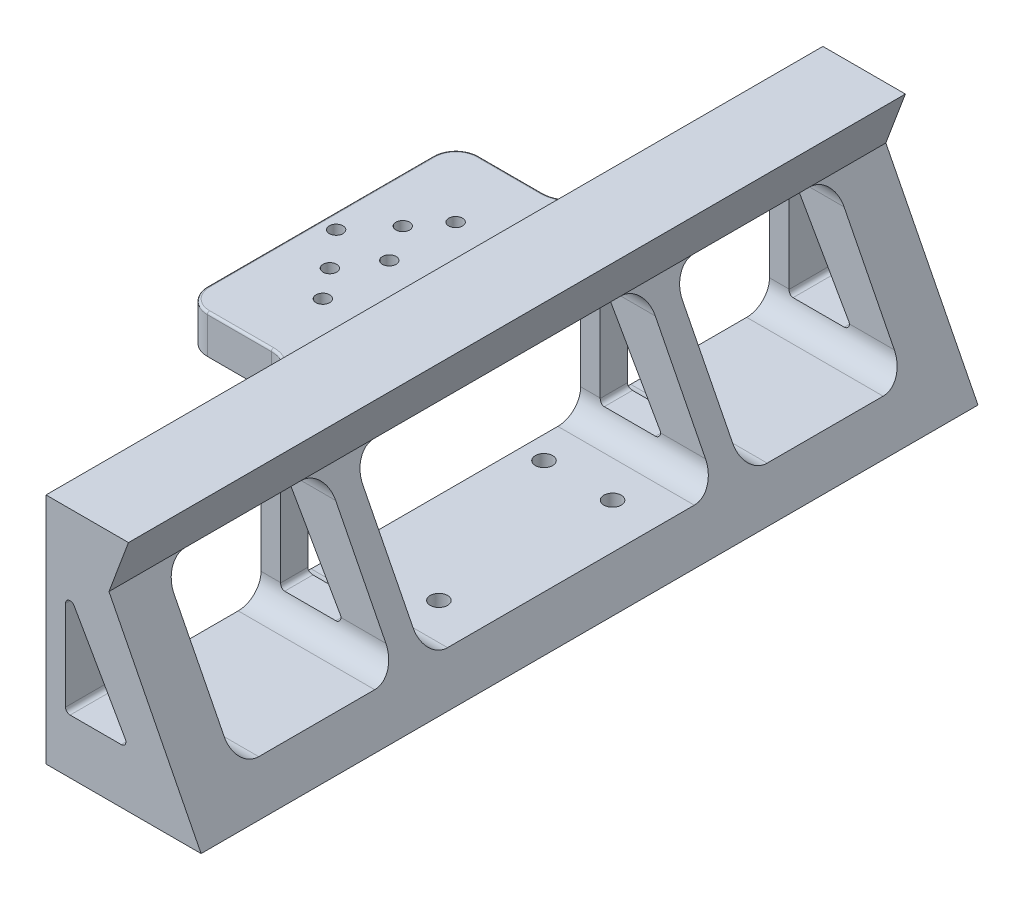
SolidWorks part; units mm, degrees
ref_plane "前视基准面" through (0, 0, 0) normal (0, 0, 1) x (1, 0, 0)
ref_plane "上视基准面" through (0, 0, 0) normal (0, 1, 0) x (1, 0, 0)
ref_plane "右视基准面" through (0, 0, 0) normal (1, 0, 0) x (0, 0, -1)
other "Configuration Table"
sketch "草图1" plane through (0, 0, 0) normal (0, 0, 1) x (1, 0, 0)
  line L0 (0, 0) -> (4315.6784, 0) construction
  line L1 (0, 0) -> (0, -4315.6784) construction
  line L2 (-37.5, 10.53) -> (-3.5592, 10.53)
  line L3 (-37.5, 10.53) -> (-37.5, 61.531)
  line L13 (-19.4493, 61.531) -> (-23.7237, 50.112)
  line L14 (-23.7237, 50.112) -> (-8.2985, 19.8329)
  line L15 (-8.2985, 19.8329) -> (-3.5592, 10.53)
  line L17 (-37.5, 61.531) -> (-19.4493, 61.531)
  point P5 (0, 0)
  point P6 (0, 0)
  point P8 (0, 0)
  point P10 (0, 0)
  point P11 (0, 0)
  point P13 (0, 0)
  point P14 (-19.4493, 61.531)
  point P17 (-23.7237, 50.112)
  dimension "D2" = 51.001
extrude "凸台-拉伸1" add sketch "草图1" along normal mid plane 170
sketch "草图2" plane through (-37.5, 0, 0) normal (-1, 0, 0) x (0, 0, 1)
  line L0 (0, -16.6592) -> (0, 83.0396) construction
  line L1 (-70, 58.531) -> (70, 58.531) construction
  line L2 (-29.6831, 58.531) -> (29.6831, 58.531)
  line L3 (-29.6831, 58.531) -> (-29.6831, 50.112)
  line L4 (-29.6831, 50.112) -> (29.6831, 50.112)
  line L5 (29.6831, 58.531) -> (29.6831, 50.112)
  line L6 (85, 50.112) -> (-85, 50.112) construction
extrude "凸台-拉伸2" add sketch "草图2" along normal blind 25
fillet "圆角1" radius 6 2 edges at (-37.5, 54.3215, 29.6831) (-37.5, 54.3215, -29.6831)
fillet "圆角2" radius 5 2 edges at (-62.5, 54.3215, 29.6831) (-62.5, 54.3215, -29.6831)
sketch "草图4" plane through (0, 58.531, 0) normal (0, 1, 0) x (1, 0, 0)
  circle A0 centre (-47.3875, 14.5262) radius 1.5
  circle A1 centre (-52.4079, 7.9763) radius 1.5
  circle A2 centre (-59.0183, 0) radius 1.5
  circle A3 centre (-47.3875, 0) radius 1.5
  circle A4 centre (-52.4079, -7.9763) radius 1.5
  circle A5 centre (-47.3875, -14.5262) radius 1.5
extrude "切除-拉伸1" cut sketch "草图4" against normal up to next
sketch "草图7" plane through (0, 0, 0) normal (1, 0, 0) x (0, 0, -1)
  line L0 (0, -13.4528) -> (0, 101.4472) construction
  line L1 (31.9992, 50.112) -> (-31.9992, 50.112)
  line L2 (31.9992, 50.112) -> (31.9992, 18.5261)
  line L3 (31.9992, 18.5261) -> (-31.9992, 18.5261)
  line L4 (-31.9992, 50.112) -> (-31.9992, 18.5261)
  line L5 (-85, 50.112) -> (85, 50.112) construction
  line L6 (37.94, 18.5261) -> (73.3146, 18.5261)
  line L7 (-37.94, 50.112) -> (-73.3146, 50.112)
  line L8 (-37.94, 50.112) -> (-37.94, 18.5261)
  line L9 (-37.94, 18.5261) -> (-73.3146, 18.5261)
  line L10 (-73.3146, 50.112) -> (-73.3146, 18.5261)
  line L11 (73.3146, 50.112) -> (73.3146, 18.5261)
  line L12 (37.94, 50.112) -> (73.3146, 50.112)
  line L13 (37.94, 50.112) -> (37.94, 18.5261)
extrude "切除-拉伸2" cut sketch "草图7" against normal through all
fillet "圆角3" radius 5 12 edges at (-22.5664, 18.5261, 37.94) (-22.5664, 18.5261, -31.9992) (-22.5664, 18.5261, -73.3146) (-22.5664, 18.5261, -37.94) (-22.5664, 18.5261, 31.9992) (-22.5664, 18.5261, 73.3146) (-30.6119, 50.112, 31.9992) (-30.6119, 50.112, -31.9992) (-30.6119, 50.112, -73.3146) (-30.6119, 50.112, -37.94) (-30.6119, 50.112, 37.94) (-30.6119, 50.112, 73.3146)
fillet "圆角4" radius 0.5 7 edges at (-39.2574, 58.531, -31.4405) (-50.5, 58.531, -29.6831) (-61.0355, 58.531, -28.2187) (-62.5, 58.531, 0) (-61.0355, 58.531, 28.2187) (-50.5, 58.531, 29.6831) (-39.2574, 58.531, 31.4405)
sketch "草图8" plane through (0, 0, 85) normal (0, 0, 1) x (1, 0, 0)
  line L0 (-32.2225, 22.4565) -> (-21.0155, 22.4565)
  line L1 (-20.1466, 23.9515) -> (-31.3536, 43.6219)
  line L2 (-33.2225, 43.1268) -> (-33.2225, 23.4565)
  arc A0 (-31.3536, 43.6219) -> (-33.2225, 43.1268) centre (-32.2225, 43.1268) ccw
  arc A1 (-32.2225, 22.4565) -> (-33.2225, 23.4565) centre (-32.2225, 23.4565) cw
  arc A2 (-21.0155, 22.4565) -> (-20.1466, 23.9515) centre (-21.0155, 23.4565) ccw
  dimension "D1" = 1
extrude "切除-拉伸3" cut sketch "草图8" against normal through all both and the other way through all
sketch "草图9" plane through (0, 18.5261, 0) normal (0, 1, 0) x (1, 0, 0)
  line L0 (-13.2181, 0) -> (49986.7819, 0) construction
  line L1 (-7.6327, 26.9992) -> (-7.6327, -26.9992) construction
  circle A0 centre (-32.5277, -19) radius 1.9
  circle A1 centre (-32.5277, 19) radius 1.9
  circle A2 centre (-17.5277, 19) radius 1.9
  circle A3 centre (-17.5277, -19) radius 1.9
  point P4 (-7.6327, 0)
  dimension "D1" = 3.8
  dimension "D2" = 38
  dimension "D3" = 2
extrude "切除-拉伸4" cut sketch "草图9" against normal blind 28
